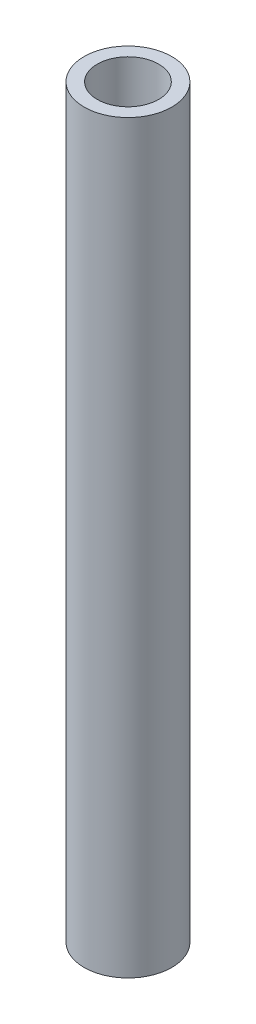
SolidWorks part; units mm, degrees
ref_plane "Front Plane" through (0, 0, 0) normal (0, 0, 1) x (1, 0, 0)
ref_plane "Top Plane" through (0, 0, 0) normal (0, 1, 0) x (1, 0, 0)
ref_plane "Right Plane" through (0, 0, 0) normal (1, 0, 0) x (0, 0, -1)
sketch "Sketch2" plane through (0, 0, 0) normal (0, 1, 0) x (1, 0, 0)
  circle A0 centre (0, 0) radius 3.5
  circle A1 centre (0, 0) radius 5
  dimension "D1" = 7
  dimension "D2" = 10
extrude "Boss-Extrude1" add sketch "Sketch2" along normal blind 85
